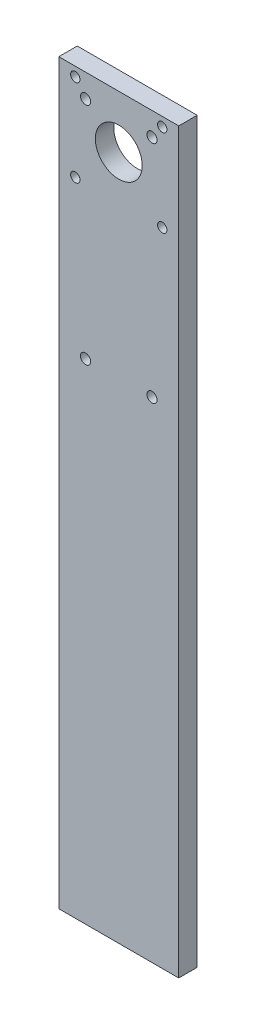
SolidWorks part; units mm, degrees
ref_plane "Front Plane" through (0, 0, 0) normal (0, 0, 1) x (1, 0, 0)
ref_plane "Top Plane" through (0, 0, 0) normal (0, 1, 0) x (1, 0, 0)
ref_plane "Right Plane" through (0, 0, 0) normal (1, 0, 0) x (0, 0, -1)
sketch "Sketch1" plane through (0, 0, 0) normal (0, 0, 1) x (1, 0, 0)
  line L0 (0, -106) -> (0, -123.4646) construction
  line L1 (0, 28.575) -> (0, -371.425) construction
  line L8 (23.5712, -23.5712) -> (-23.5712, -23.5712) construction
  line L9 (23.5712, -23.5712) -> (23.5712, 23.5712) construction
  line L10 (23.5712, 23.5712) -> (-23.5712, 23.5712) construction
  line L11 (-23.5712, -23.5712) -> (-23.5712, 23.5712) construction
  line L12 (23.5712, -23.5712) -> (-23.5712, 23.5712) construction
  line L13 (23.5712, 23.5712) -> (-23.5712, -23.5712) construction
  line L15 (-32.5, -371.425) -> (32.5, -371.425)
  line L16 (-32.5, -371.425) -> (-32.5, 28.575)
  line L17 (-32.5, 28.575) -> (32.5, 28.575)
  line L18 (32.5, -371.425) -> (32.5, 28.575)
  line L19 (-32.5, -371.425) -> (32.5, 28.575) construction
  line L20 (-32.5, 28.575) -> (32.5, -371.425) construction
  circle A0 centre (-23.5712, 23.5712) radius 2.54
  circle A1 centre (23.5712, 23.5712) radius 2.54
  circle A2 centre (23.5712, -23.5712) radius 2.54
  circle A3 centre (-23.5712, -23.5712) radius 2.54
  circle A8 centre (0, 0) radius 12.7
  circle A9 centre (18, 16) radius 2.75
  circle A10 centre (0, 16) radius 18 construction
  circle A11 centre (-18, 16) radius 2.75
  circle A12 centre (18, -106) radius 2.75
  circle A13 centre (-18, -106) radius 2.75
  point P0 (0, 0)
  point P8 (0, 0)
  point P37 (0, -171.425)
  dimension "D5" = 5.08
  dimension "D8" = 5.5
  dimension "D9" = 400
  dimension "D2" = 25.4
  dimension "D3" = 47.1424
  dimension "D4" = 47.1424
  dimension "D10" = 65
extrude "Boss-Extrude1" add sketch "Sketch1" along normal blind 10
